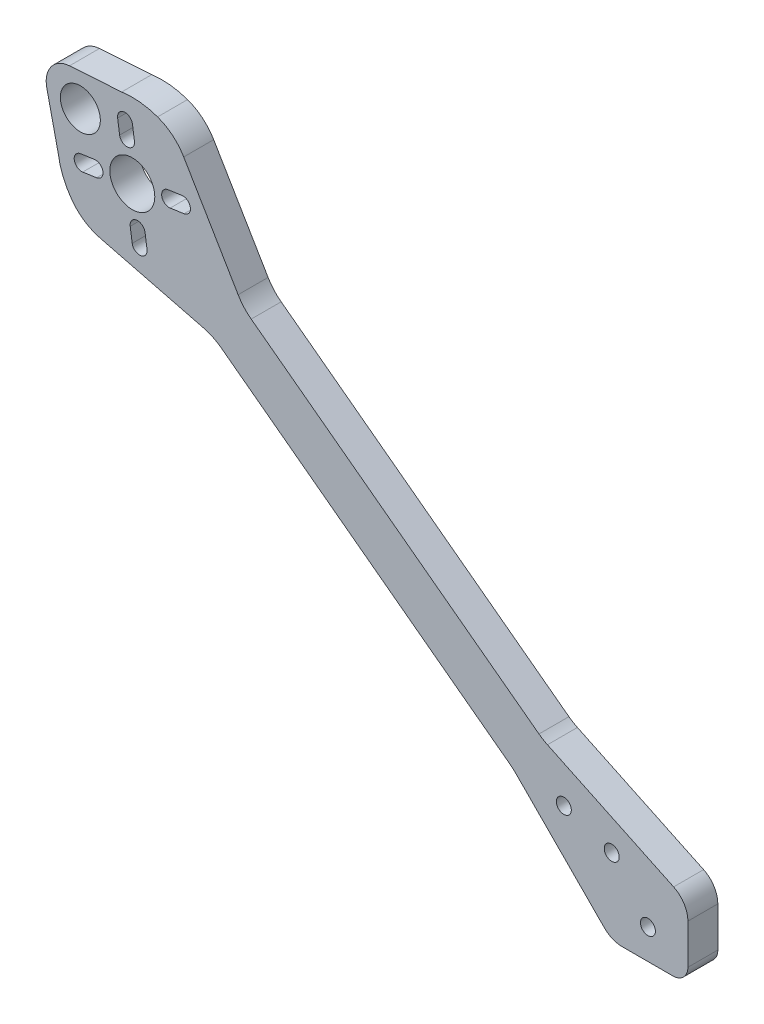
SolidWorks part; units mm, degrees
ref_plane "Alzado" through (0, 0, 0) normal (0, 0, 1) x (1, 0, 0)
ref_plane "Planta" through (0, 0, 0) normal (0, 1, 0) x (1, 0, 0)
ref_plane "Vista lateral" through (0, 0, 0) normal (1, 0, 0) x (0, 0, -1)
sketch "Croquis1" plane through (0, 0, 0) normal (0, 0, 1) x (1, 0, 0)
  line L0 (0, 0) -> (-129.6939, 97.0747) construction
  line L1 (8, 6) -> (-8, 6) construction
  line L2 (8, 6) -> (8, -6) construction
  line L3 (8, -6) -> (-8, -6) construction
  line L4 (-8, 6) -> (-8, -6) construction
  line L5 (8, 6) -> (-8, -6) construction
  line L6 (8, -6) -> (-8, 6) construction
  line L7 (24.85, 18.6) -> (-24.85, 18.6) construction
  line L8 (24.85, 18.6) -> (24.85, -18.6) construction
  line L9 (24.85, -18.6) -> (-24.85, -18.6) construction
  line L10 (-24.85, 18.6) -> (-24.85, -18.6) construction
  line L11 (24.85, 18.6) -> (-24.85, -18.6) construction
  line L12 (24.85, -18.6) -> (-24.85, 18.6) construction
  line L17 (-20.3743, -15.25) -> (20.3743, 15.25) construction
  line L18 (-20.3743, 15.25) -> (20.3743, -15.25) construction
  line L19 (0, 3) -> (0, 11.0059)
  line L20 (-3, 0) -> (-13.1644, 0)
  line L21 (-32.0232, 23.9691) -> (-29.027, 27.972) construction
  line L22 (-2.8522, 15.5211) -> (-28.1277, 27.5441)
  line L23 (-32.0232, 23.9691) -> (-35.0193, 19.9662) construction
  line L24 (-16.7174, 1.482) -> (-34.4983, 19.44)
  line L25 (-111.2806, 83.2925) -> (-112.9535, 94.9228) construction
  line L31 (-114.4382, 94.7092) -> (-111.4688, 95.1363) construction
  line L32 (-111.4688, 95.1363) -> (-111.2552, 93.6516) construction
  line L33 (-113.6124, 88.9683) -> (-110.643, 89.3954) construction
  line L34 (-110.643, 89.3954) -> (-110.8566, 90.8802) construction
  line L35 (-111.2552, 93.6516) -> (-110.8566, 90.8802)
  line L36 (-113.6124, 88.9683) -> (-113.826, 90.453) construction
  line L37 (-114.4382, 94.7092) -> (-114.2246, 93.2245) construction
  line L38 (-114.2246, 93.2245) -> (-113.826, 90.453)
  line L39 (-100.9214, 83.2671) -> (-103.6929, 82.8685)
  line L40 (-101.3485, 86.2366) -> (-104.12, 85.8379)
  line L41 (-111.2806, 83.2925) -> (-99.6503, 84.9654) construction
  line L42 (-99.8638, 86.4501) -> (-99.4367, 83.4807) construction
  line L43 (-99.4367, 83.4807) -> (-100.9214, 83.2671) construction
  line L44 (-105.6047, 85.6244) -> (-105.1776, 82.6549) construction
  line L45 (-105.1776, 82.6549) -> (-103.6929, 82.8685) construction
  line L46 (-105.6047, 85.6244) -> (-104.12, 85.8379) construction
  line L47 (-99.8638, 86.4501) -> (-101.3485, 86.2366) construction
  line L48 (-111.3059, 72.9333) -> (-111.7046, 75.7048)
  line L49 (-108.3365, 73.3605) -> (-108.7351, 76.132)
  line L50 (-111.2806, 83.2925) -> (-109.6076, 71.6622) construction
  line L51 (-108.1229, 71.8758) -> (-111.0923, 71.4486) construction
  line L52 (-111.0923, 71.4486) -> (-111.3059, 72.9333) construction
  line L53 (-108.9487, 77.6167) -> (-111.9181, 77.1895) construction
  line L54 (-111.9181, 77.1895) -> (-111.7046, 75.7048) construction
  line L55 (-108.9487, 77.6167) -> (-108.7351, 76.132) construction
  line L56 (-108.1229, 71.8758) -> (-108.3365, 73.3605) construction
  line L57 (-121.6397, 83.3178) -> (-118.8682, 83.7165)
  line L58 (-121.2126, 80.3484) -> (-118.4411, 80.7471)
  line L59 (-111.2806, 83.2925) -> (-122.9108, 81.6195) construction
  line L60 (-122.6973, 80.1348) -> (-123.1244, 83.1043) construction
  line L61 (-123.1244, 83.1043) -> (-121.6397, 83.3178) construction
  line L62 (-116.9564, 80.9606) -> (-117.3835, 83.9301) construction
  line L63 (-117.3835, 83.9301) -> (-118.8682, 83.7165) construction
  line L64 (-116.9564, 80.9606) -> (-118.4411, 80.7471) construction
  line L65 (-122.6973, 80.1348) -> (-121.2126, 80.3484) construction
  line L66 (-111.2806, 83.2925) -> (-120.269, 71.2838) construction
  line L67 (-122.9108, 81.6195) -> (-126.1277, 81.1568) construction
  line L68 (-128.4167, 91.3737) -> (-126.1277, 81.1568)
  line L69 (-109.6076, 71.6622) -> (-109.1449, 68.4453) construction
  line L70 (-35.6121, 20.4099) -> (-93.4616, 63.7097)
  line L72 (-29.8244, 28.5687) -> (-87.1885, 71.5052)
  line L74 (-123.864, 97.4561) -> (-113.4162, 98.1397)
  line L75 (-95.0628, 64.9082) -> (-92.0666, 68.9111) construction
  line L76 (-15.25, 15.25) -> (15.25, 15.25) construction
  line L77 (-15.25, 15.25) -> (-15.25, -15.25) construction
  line L78 (-15.25, -15.25) -> (15.25, -15.25) construction
  line L79 (15.25, 15.25) -> (15.25, -15.25) construction
  line L80 (-15.25, 15.25) -> (15.25, -15.25) construction
  line L81 (-15.25, -15.25) -> (15.25, 15.25) construction
  line L82 (-117.7732, 70.6525) -> (-97.0017, 65.3986)
  line L83 (-100.983, 93.0845) -> (-90.0876, 74.636)
  line L84 (-87.4694, 71.7155) -> (-87.1885, 71.5052)
  circle A0 centre (-24.85, 18.6) radius 1.5
  circle A2 centre (-8, 6) radius 1.5
  circle A12 centre (-121.6881, 91.0824) radius 4
  circle A13 centre (-111.2806, 83.2925) radius 4.5
  arc A16 (-114.2246, 93.2245) -> (-111.2552, 93.6516) centre (-112.7399, 93.4381) cw
  arc A17 (-110.8566, 90.8802) -> (-113.826, 90.453) centre (-112.3413, 90.6666) cw
  arc A18 (-101.3485, 86.2366) -> (-100.9214, 83.2671) centre (-101.135, 84.7519) cw
  arc A19 (-103.6929, 82.8685) -> (-104.12, 85.8379) centre (-103.9065, 84.3532) cw
  arc A20 (-108.3365, 73.3605) -> (-111.3059, 72.9333) centre (-109.8212, 73.1469) cw
  arc A21 (-111.7046, 75.7048) -> (-108.7351, 76.132) centre (-110.2198, 75.9184) cw
  arc A22 (-121.2126, 80.3484) -> (-121.6397, 83.3178) centre (-121.4261, 81.8331) cw
  arc A23 (-118.8682, 83.7165) -> (-118.4411, 80.7471) centre (-118.6547, 82.2318) cw
  circle A24 centre (-111.2806, 83.2925) radius 15 construction
  arc A25 (-126.1277, 81.1568) -> (-123.4019, 74.4566) centre (-111.2806, 83.2925) ccw
  arc A27 (-123.864, 97.4561) -> (-128.4167, 91.3737) centre (-123.5376, 92.4668) ccw
  arc A28 (-35.6121, 20.4099) -> (-34.4983, 19.44) centre (-41.6044, 12.4041) cw
  arc A29 (-29.8244, 28.5687) -> (-28.1277, 27.5441) centre (-23.8321, 36.5745) ccw
  arc A34 (-13.1644, 0) -> (-16.7174, 1.482) centre (-13.1644, 5) cw
  arc A35 (0, 11.0059) -> (-2.8522, 15.5211) centre (-5, 11.0059) ccw
  arc A36 (0, 3) -> (-3, 0) centre (-3, 3) cw
  circle A37 centre (-15.25, 15.25) radius 1.5
  arc A38 (-97.0017, 65.3986) -> (-93.4616, 63.7097) centre (-99.4539, 55.7039) cw
  arc A39 (-117.7732, 70.6525) -> (-123.4019, 74.4566) centre (-115.321, 80.3472) cw
  arc A40 (-113.4162, 98.1397) -> (-106.2194, 97.4128) centre (-111.2806, 83.2925) cw
  arc A41 (-100.983, 93.0845) -> (-106.2194, 97.4128) centre (-109.5935, 87.9993) ccw
  arc A42 (-90.0876, 74.636) -> (-87.4694, 71.7155) centre (-81.4771, 79.7213) ccw
  point P0 (0, 0)
  point P6 (0, 0)
  point P11 (0, 0)
  point P85 (-111.2806, 83.2925)
  point P104 (-96.4334, 85.4282)
  point P107 (-89.0705, 72.9139)
  point P110 (-95.0628, 64.9082)
  point P116 (-15.25, 0)
  point P119 (0, 14.1644)
  dimension "D6" = 162
  dimension "D9" = 10
  dimension "D10" = 13
  dimension "D15" = 10
  dimension "D14" = 5
  dimension "D16" = 5
  dimension "D17" = 3
  dimension "D20" = 10
  dimension "D1" = 16
  dimension "D2" = 12
  dimension "D3" = 49.7
  dimension "D4" = 37.2
  dimension "D5" = 40.7487
  dimension "D7" = 15.25
  dimension "D8" = 40
  dimension "D11" = 45
  dimension "D12" = 4
  dimension "D13" = 75
  dimension "D18" = 30.5
  dimension "D19" = 30.5
extrude "Saliente-Extruir1" add sketch "Croquis1" along normal blind 6
